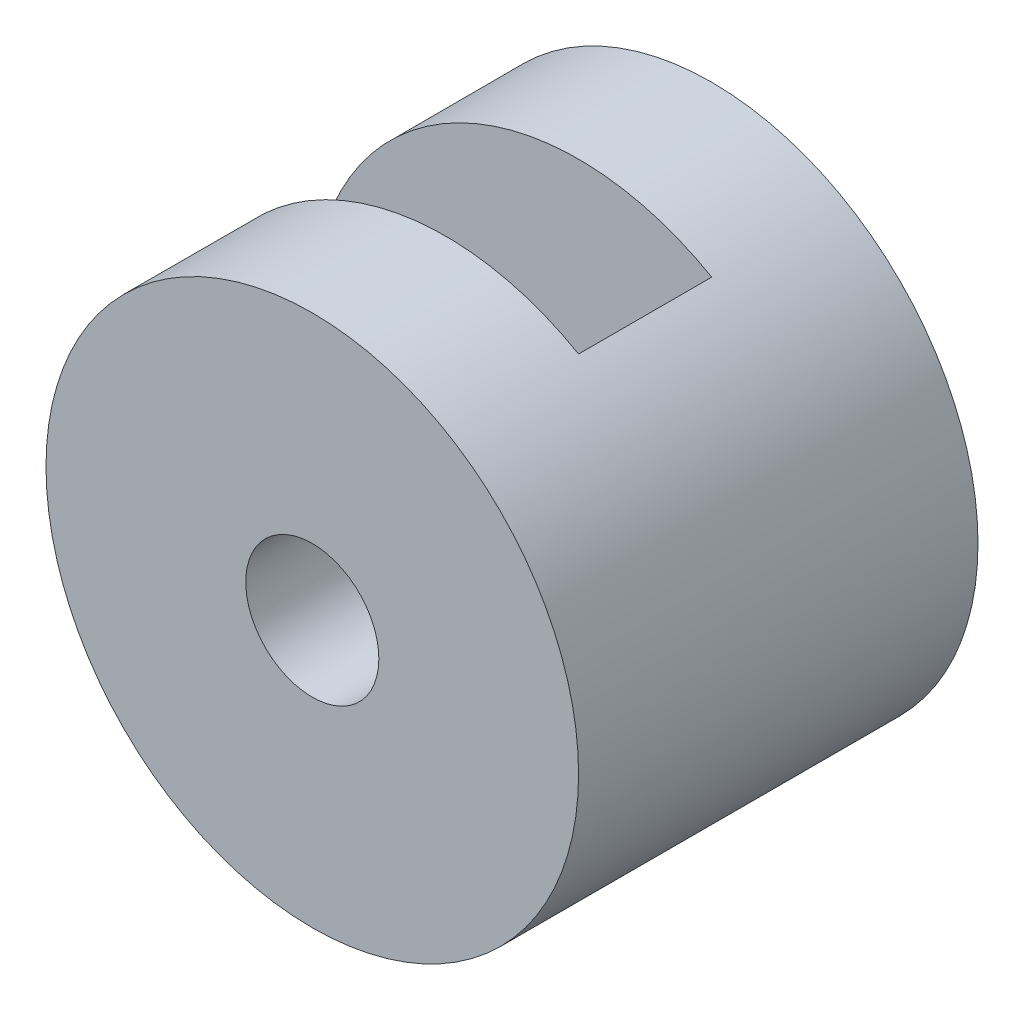
SolidWorks part; units mm, degrees
ref_plane "Alzado" through (0, 0, 0) normal (0, 0, 1) x (1, 0, 0)
ref_plane "Planta" through (0, 0, 0) normal (0, 1, 0) x (1, 0, 0)
ref_plane "Vista lateral" through (0, 0, 0) normal (1, 0, 0) x (0, 0, -1)
sketch "Croquis1" plane through (0, 0, 0) normal (0, 0, 1) x (1, 0, 0)
  circle A0 centre (0, 0) radius 20
  circle A1 centre (0, 0) radius 5
  dimension "D1" = 40
  dimension "D2" = 10
extrude "Saliente-Extruir1" add sketch "Croquis1" along normal mid plane 30
sketch "Croquis6" plane through (0, 0, 0) normal (0, 0, 1) x (1, 0, 0)
  circle A0 centre (0, 0) radius 10
  dimension "D1" = 20
extrude "Cortar-Extruir6" cut sketch "Croquis6" against normal mid plane 10
sketch "Croquis7" plane through (0, 0, 0) normal (1, 0, 0) x (0, 0, -1)
  line L0 (15, 20) -> (-15, 20) construction
  line L1 (5, 20) -> (-5, 20)
  line L2 (5, 20) -> (5, -10)
  line L3 (5, -10) -> (-5, -10)
  line L4 (-5, 20) -> (-5, -10)
  point P4 (0, 20)
  dimension "D1" = 10
  dimension "D2" = 10
extrude "Cortar-Extruir7" cut sketch "Croquis7" against normal blind 36
sketch "Croquis8" plane through (0, 0, 0) normal (-1, 0, 0) x (0, 0, 1)
  line L0 (5, 10) -> (5, -10) construction
  line L1 (-5, 20) -> (5, 20)
  line L2 (-5, 20) -> (-5, 0)
  line L3 (-5, 0) -> (5, 0)
  line L4 (5, 20) -> (5, 0)
  point P7 (0, 0)
extrude "Cortar-Extruir9" cut sketch "Croquis8" against normal blind 10
